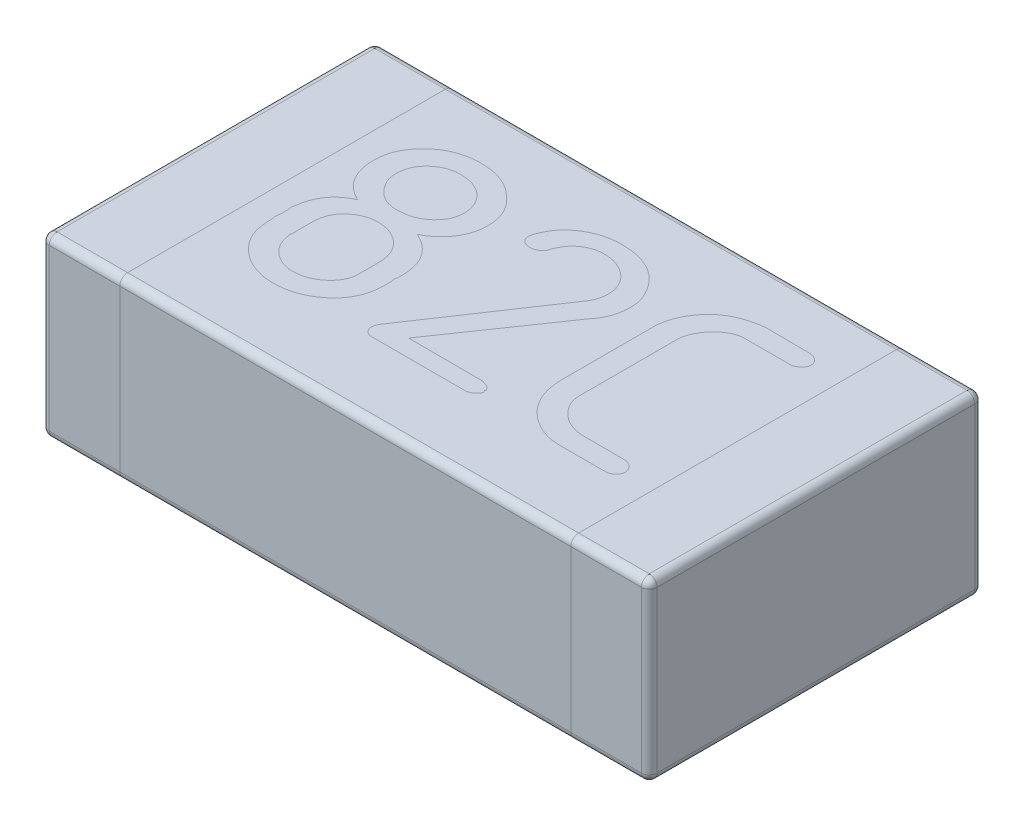
SolidWorks part; units mm, degrees
ref_plane "Front Plane" through (0, 0, 0) normal (0, 0, 1) x (1, 0, 0)
ref_plane "Top Plane" through (0, 0, 0) normal (0, 1, 0) x (1, 0, 0)
ref_plane "Right Plane" through (0, 0, 0) normal (1, 0, 0) x (0, 0, -1)
sketch "Sketch1" plane through (0, 0, 0) normal (0, 1, 0) x (1, 0, 0)
  line L1 (-0.755, -0.425) -> (0.755, -0.425)
  line L2 (-0.775, -0.405) -> (-0.775, 0.405)
  line L3 (-0.755, 0.425) -> (0.755, 0.425)
  line L4 (0.775, -0.405) -> (0.775, 0.405)
  line L5 (-0.775, -0.425) -> (0.775, 0.425) construction
  line L6 (-0.775, 0.425) -> (0.775, -0.425) construction
  arc A4 (-0.775, -0.405) -> (-0.755, -0.425) centre (-0.755, -0.405) ccw
  arc A5 (0.755, -0.425) -> (0.775, -0.405) centre (0.755, -0.405) ccw
  arc A6 (0.775, 0.405) -> (0.755, 0.425) centre (0.755, 0.405) ccw
  arc A7 (-0.755, 0.425) -> (-0.775, 0.405) centre (-0.755, 0.405) ccw
  point P0 (0, 0)
  dimension "D4" = 0.02
  dimension "D1" = 1.55
  dimension "D2" = 0.85
extrude "Boss-Extrude1" add sketch "Sketch1" along normal mid plane 0.45
sketch "Sketch3" plane through (0, 0.225, 0) normal (0, 1, 0) x (1, 0, 0)
  line L0 (-0.575, 0) -> (0.575, 0) construction
  line L1 (-0.575, -0.5133) -> (-0.575, 0.5133)
  line L2 (0.575, -0.5133) -> (0.575, 0.5133)
  line L3 (0, -0.25) -> (0, 0.25) construction
  line L6 (-0.575, -0.25) -> (0.575, -0.25) construction
  text T0 "<b>82C</b>" font "SWIsop1" height 0.53
  point P4 (0, 0)
  point P8 (-0.575, 0)
  point P11 (0.575, 0)
  point P14 (0, 0)
  point P17 (0, -0.25)
  dimension "D1" = 1.15
  dimension "D2" = 0.5
sketch "Sketch4" plane through (0, 0, 0.425) normal (0, 0, 1) x (1, 0, 0)
  line L0 (-0.575, 0.225) -> (-0.575, -0.5946)
  line L1 (0.575, 0.225) -> (0.575, -0.5946)
sketch "Sketch5" plane through (0, 0, -0.425) normal (0, 0, -1) x (-1, 0, 0)
  line L0 (-0.575, 0.225) -> (-0.575, -0.5946) construction
  line L1 (-0.575, 0.225) -> (-0.575, -0.5946)
  line L2 (0.575, 0.225) -> (0.575, -0.5946) construction
  line L3 (0.575, 0.225) -> (0.575, -0.5946)
sketch "Sketch6" plane through (0, -0.225, 0) normal (0, -1, 0) x (1, 0, 0)
  line L0 (0.575, 0.5133) -> (0.575, -0.5133) construction
  line L1 (-0.575, 0.5133) -> (-0.575, -0.5133) construction
  line L2 (0.575, 0.5133) -> (0.575, -0.5133)
  line L3 (-0.575, 0.5133) -> (-0.575, -0.5133)
split line "Split Line2"
split line "Split Line3"
split line "Split Line4"
split line "Split Line5"
fillet "Fillet2" radius 0.02 24 edges at (-0.665, -0.225, 0.425) (0, -0.225, 0.425) (0.665, -0.225, 0.425) (-0.7691, -0.225, 0.4191) (-0.775, -0.225, 0) (-0.7691, -0.225, -0.4191) (0.665, -0.225, -0.425) (0, -0.225, -0.425) (-0.665, -0.225, -0.425) (0.7691, -0.225, -0.4191) (0.775, -0.225, 0) (0.7691, -0.225, 0.4191) (-0.7691, 0.225, 0.4191) (-0.775, 0.225, 0) (-0.7691, 0.225, -0.4191) (0.665, 0.225, -0.425) (0, 0.225, -0.425) (-0.665, 0.225, -0.425) (0.7691, 0.225, -0.4191) (0.775, 0.225, 0) (0.7691, 0.225, 0.4191) (-0.665, 0.225, 0.425) (0, 0.225, 0.425) (0.665, 0.225, 0.425)
